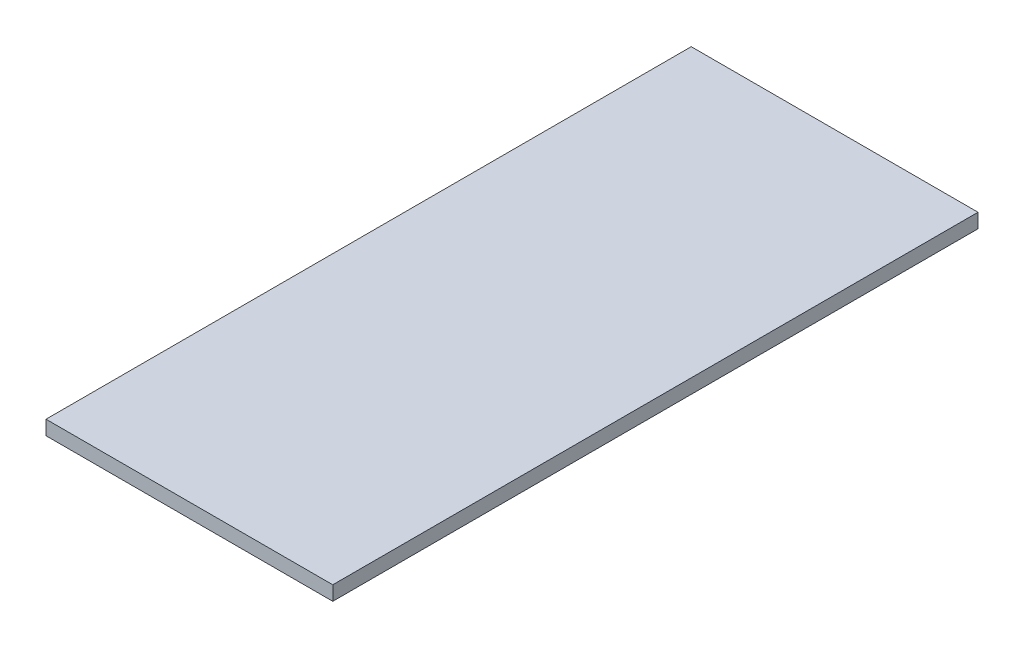
SolidWorks part; units mm, degrees
ref_plane "Front Plane" through (0, 0, 0) normal (0, 0, 1) x (1, 0, 0)
ref_plane "Top Plane" through (0, 0, 0) normal (0, 1, 0) x (1, 0, 0)
ref_plane "Right Plane" through (0, 0, 0) normal (1, 0, 0) x (0, 0, -1)
sketch "Sketch1" plane through (0, 0, 0) normal (0, 1, 0) x (1, 0, 0)
  line L1 (0, 0) -> (50.8, 0)
  line L2 (0, 0) -> (0, 114.3)
  line L3 (0, 114.3) -> (50.8, 114.3)
  line L4 (50.8, 0) -> (50.8, 114.3)
  dimension "D1" = 114.3
  dimension "D2" = 50.8
extrude "Boss-Extrude1" add sketch "Sketch1" along normal blind 2.54
